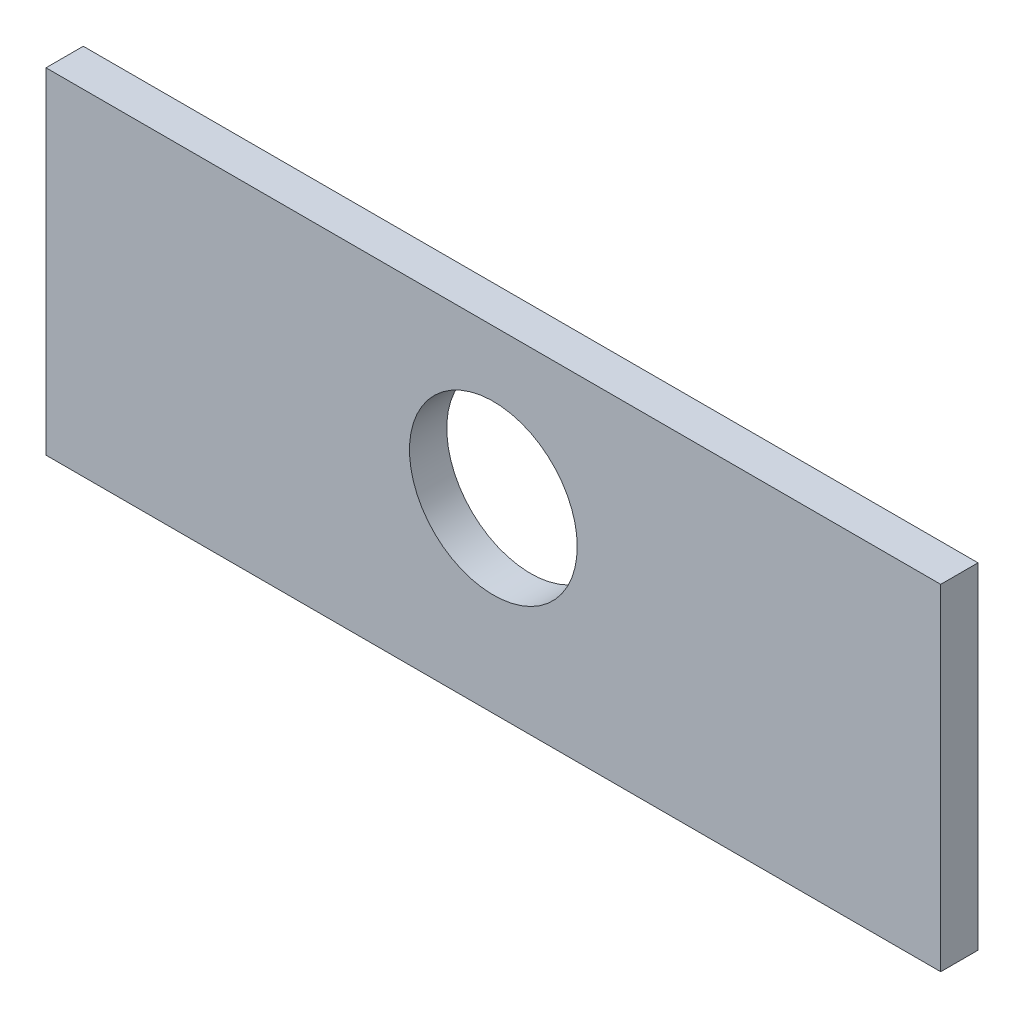
SolidWorks part; units mm, degrees
ref_plane "Alzado" through (0, 0, 0) normal (0, 0, 1) x (1, 0, 0)
ref_plane "Planta" through (0, 0, 0) normal (0, 1, 0) x (1, 0, 0)
ref_plane "Vista lateral" through (0, 0, 0) normal (1, 0, 0) x (0, 0, -1)
sketch "Croquis1" plane through (0, 0, 0) normal (0, 0, 1) x (1, 0, 0)
  line L0 (120, 0) -> (120, 10) construction
  line L1 (0, 0) -> (240, 0)
  line L2 (0, 0) -> (0, 90)
  line L3 (0, 90) -> (240, 90)
  line L4 (240, 0) -> (240, 90)
  line L5 (120, 10) -> (120, 90) construction
  circle A1 centre (120, 50) radius 22.5
extrude "Saliente-Extruir1" add sketch "Croquis1" along normal blind 10
